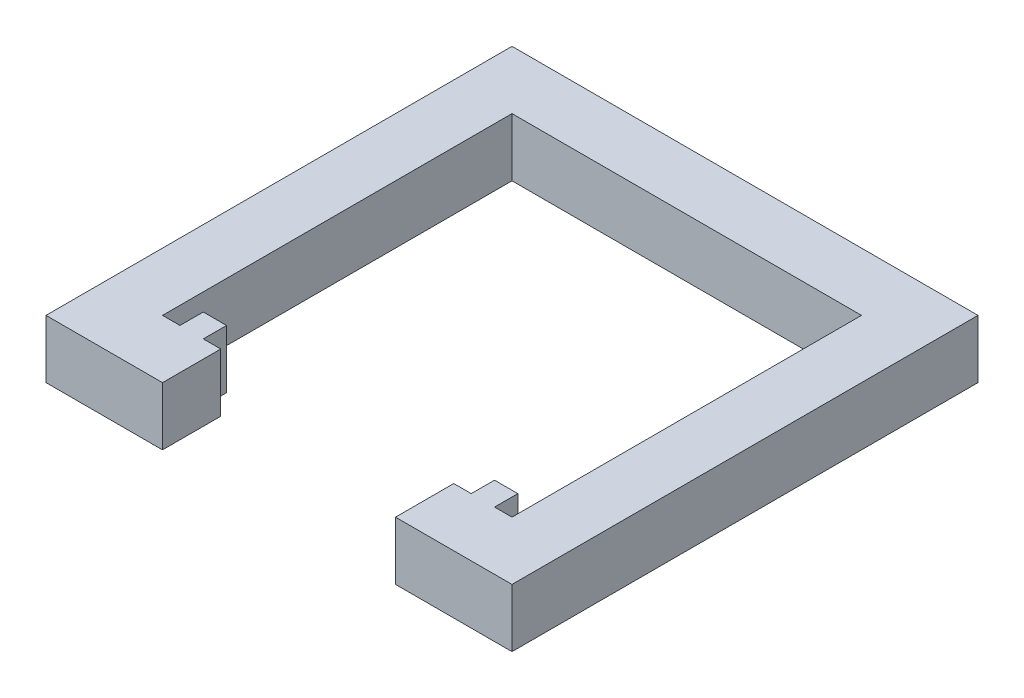
SolidWorks part; units mm, degrees
ref_plane "Front Plane" through (0, 0, 0) normal (0, 0, 1) x (1, 0, 0)
ref_plane "Top Plane" through (0, 0, 0) normal (0, 1, 0) x (1, 0, 0)
ref_plane "Right Plane" through (0, 0, 0) normal (1, 0, 0) x (0, 0, -1)
sketch "Sketch1" plane through (0, 0, 0) normal (0, 1, 0) x (1, 0, 0)
  line L9 (-151.1123, -10.9875) -> (-98.42, -10.9875)
  line L10 (-151.1123, -10.9875) -> (-151.1123, -410.9875)
  line L11 (-151.1123, -410.9875) -> (-101.1123, -410.9875)
  line L12 (-101.1123, -60.9875) -> (-101.1123, -360.9875)
  line L13 (-151.1123, -10.9875) -> (248.8877, -10.9875)
  line L14 (-151.1123, -10.9875) -> (-151.1123, -219.2785)
  line L15 (-101.1123, -60.9875) -> (198.8877, -60.9875)
  line L16 (248.8877, -10.9875) -> (248.8877, -219.2785)
  line L17 (169.9573, -10.9875) -> (248.8877, -10.9875)
  line L18 (198.8877, -60.9875) -> (198.8877, -360.9875)
  line L19 (198.8877, -410.9875) -> (248.8877, -410.9875)
  line L20 (248.8877, -10.9875) -> (248.8877, -410.9875)
  line L22 (-101.1123, -360.9875) -> (-101.1123, -410.9875)
  line L26 (198.8877, -360.9875) -> (198.8877, -410.9875)
  line L27 (198.8877, -410.9875) -> (148.8877, -410.9875)
  line L28 (-101.1123, -360.9875) -> (-51.1123, -360.9875)
  line L29 (-151.1123, -380.152) -> (-151.1123, -410.9875)
  line L30 (-151.1123, -410.9875) -> (-51.1123, -410.9875)
  line L31 (-51.1123, -360.9875) -> (-51.1123, -410.9875)
  line L32 (148.8877, -360.9875) -> (198.8877, -360.9875)
  line L33 (148.8877, -360.9875) -> (148.8877, -410.9875)
  line L34 (148.8877, -410.9875) -> (248.8877, -410.9875)
  line L35 (248.8877, -380.152) -> (248.8877, -410.9875)
  line L36 (-86.1123, -340.9875) -> (-66.1123, -340.9875)
  line L37 (-86.1123, -340.9875) -> (-86.1123, -360.9875)
  line L38 (-86.1123, -360.9875) -> (-66.1123, -360.9875)
  line L39 (-66.1123, -340.9875) -> (-66.1123, -360.9875)
  line L40 (163.8877, -340.9875) -> (183.8877, -340.9875)
  line L41 (163.8877, -340.9875) -> (163.8877, -360.9875)
  line L42 (163.8877, -360.9875) -> (183.8877, -360.9875)
  line L43 (183.8877, -340.9875) -> (183.8877, -360.9875)
  point P19 (-51.1123, -385.9875)
  dimension "D1" = 200
  dimension "D2" = 50
  dimension "D3" = 50
  dimension "D4" = 50
  dimension "D5" = 50
  dimension "D6" = 50
  dimension "D7" = 50
  dimension "D8" = 50
  dimension "D9" = 300
  dimension "D10" = 300
  dimension "D11" = 20
  dimension "D12" = 15
  dimension "D13" = 20
  dimension "D14" = 20
  dimension "D15" = 15
  dimension "D16" = 20
extrude "Boss-Extrude1" add sketch "Sketch1" along normal blind 50 contours L18 L26 L19 L20 L16 L13 L9 L10 L11 L22 L12 L15 | L32 L33 L27 L26 | L31 L28 L22 L30 | L39 L36 L37 L28 | L43 L40 L41 L32
equation "\"ScannerWidth\"= 800"
equation "\"ScannerLength\"= 400"
equation "\"SpineLength\"= 100"
equation "\"ScannerThickness\"= 50"
equation "\"ScannerHeight\" = 50"
equation "\"SpineWidth\"= 100"
equation "\"TrainWidth\"= 40"
equation "\"TrainLength\"=20"
equation "\"Armwidth\"= 50"
equation "\"Armlength\"=1000"
equation "\"RailWidth\"= 20"
equation "\"RailLength\"= 650"
equation "\"RailDepth\"=20"
equation "\"HeadTowerHeight\"= 450"
equation "\"HeadSeparation\"= 200"
equation "\"HeadTowerRingRailWidth\"= 20"
equation "\"HeadTowerRingRailDepth\"= 20"
equation "\"D1@Sketch1\"=\"HeadSeparation\""
equation "\"D2@Sketch1\"=\"ScannerThickness\""
equation "\"D3@Sketch1\"=\"ScannerThickness\""
equation "\"D4@Sketch1\"=\"ScannerThickness\""
equation "\"D5@Sketch1\"=\"ScannerThickness\""
equation "\"D6@Sketch1\"=\"ScannerThickness\""
equation "\"D7@Sketch1\"=\"ScannerThickness\""
equation "\"D8@Sketch1\"=\"ScannerThickness\""
equation "\"HeadLength\"= 300"
equation "\"D9@Sketch1\"=\"HeadLength\""
equation "\"D10@Sketch1\"=\"HeadLength\""
equation "\"D11@Sketch1\"=\"HeadTowerRingRailWidth\""
equation "\"D12@Sketch1\"=(\"ScannerThickness\"-\"HeadTowerRingRailWidth\")/2"
equation "\"D13@Sketch1\"=\"HeadTowerRingRailDepth\""
equation "\"D14@Sketch1\"=\"HeadTowerRingRailWidth\""
equation "\"D15@Sketch1\"=(\"ScannerThickness\"-\"HeadTowerRingRailWidth\")/2"
equation "\"D16@Sketch1\"=\"HeadTowerRingRailDepth\""
equation "\"HeadScannerHeight\"=50"
equation "\"D1@Boss-Extrude1\"=\"HeadScannerHeight\""
